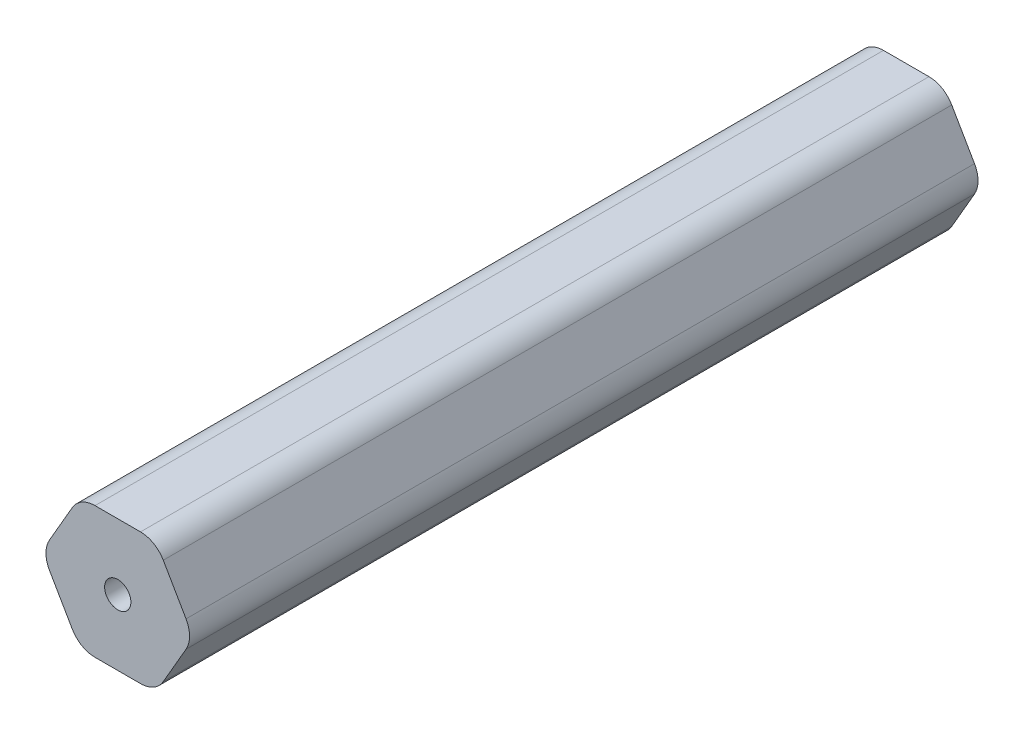
SolidWorks part; units mm, degrees
ref_plane "Front Plane" through (0, 0, 0) normal (0, 0, 1) x (1, 0, 0)
ref_plane "Top Plane" through (0, 0, 0) normal (0, 1, 0) x (1, 0, 0)
ref_plane "Right Plane" through (0, 0, 0) normal (1, 0, 0) x (0, 0, -1)
sketch "Sketch1" plane through (0, 0, 0) normal (0, 0, 1) x (1, 0, 0)
  line L1 (0.8626, -0.9345) -> (-2.8035, 5.4155)
  line L2 (-2.8035, 5.4155) -> (-10.1359, 5.4155)
  line L3 (-10.1359, 5.4155) -> (-13.8021, -0.9345)
  line L4 (-13.8021, -0.9345) -> (-10.1359, -7.2845)
  line L5 (-10.1359, -7.2845) -> (-2.8035, -7.2845)
  line L6 (-2.8035, -7.2845) -> (0.8626, -0.9345)
  circle A0 centre (-6.4697, -0.9345) radius 6.35 construction
  circle A1 centre (-6.4697, -0.9345) radius 1.27
  dimension "D1" = 12.7
extrude "Boss-Extrude1" add sketch "Sketch1" along normal blind 76.2
fillet "Fillet1" radius 2.54 6 edges at (-10.1359, -7.2845, 38.1) (-2.8035, -7.2845, 38.1) (0.8626, -0.9345, 38.1) (-13.8021, -0.9345, 38.1) (-10.1359, 5.4155, 38.1) (-2.8035, 5.4155, 38.1)
